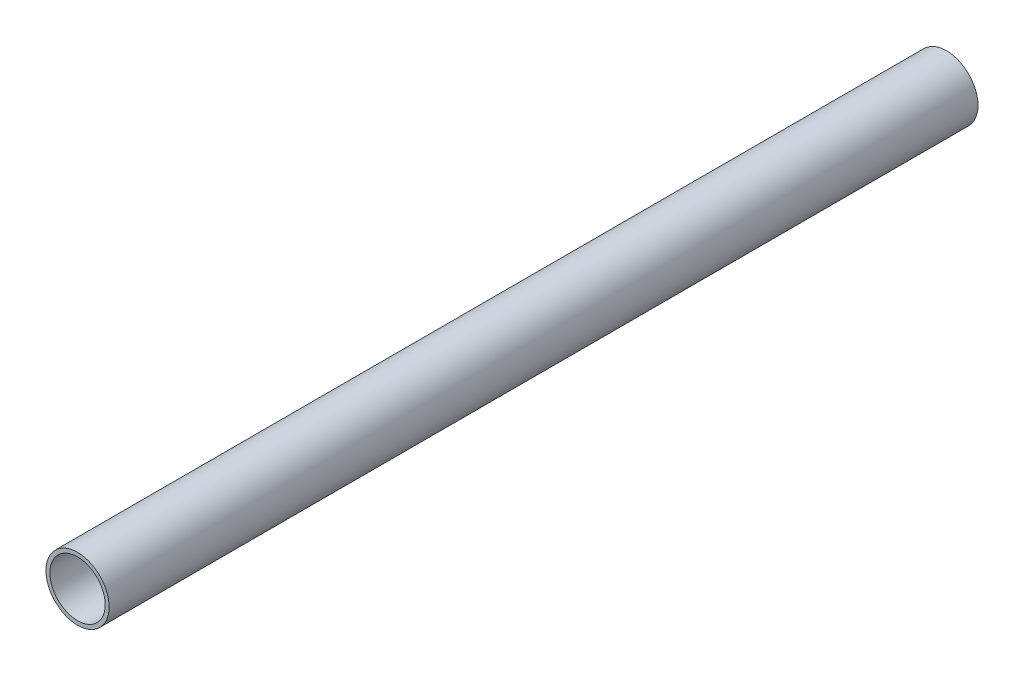
SolidWorks part; units mm, degrees
material "Thornel Mat VMA"
ref_plane "前视基准面" through (0, 0, 0) normal (0, 0, 1) x (1, 0, 0)
ref_plane "上视基准面" through (0, 0, 0) normal (0, 1, 0) x (1, 0, 0)
ref_plane "右视基准面" through (0, 0, 0) normal (1, 0, 0) x (0, 0, -1)
sketch "草图1" plane through (0, 0, 0) normal (0, 0, 1) x (1, 0, 0)
  circle A0 centre (0, 0) radius 8
  circle A1 centre (0, 0) radius 7
  dimension "D1" = 16
  dimension "D2" = 1
extrude "凸台-拉伸1" add sketch "草图1" along normal mid plane 220
